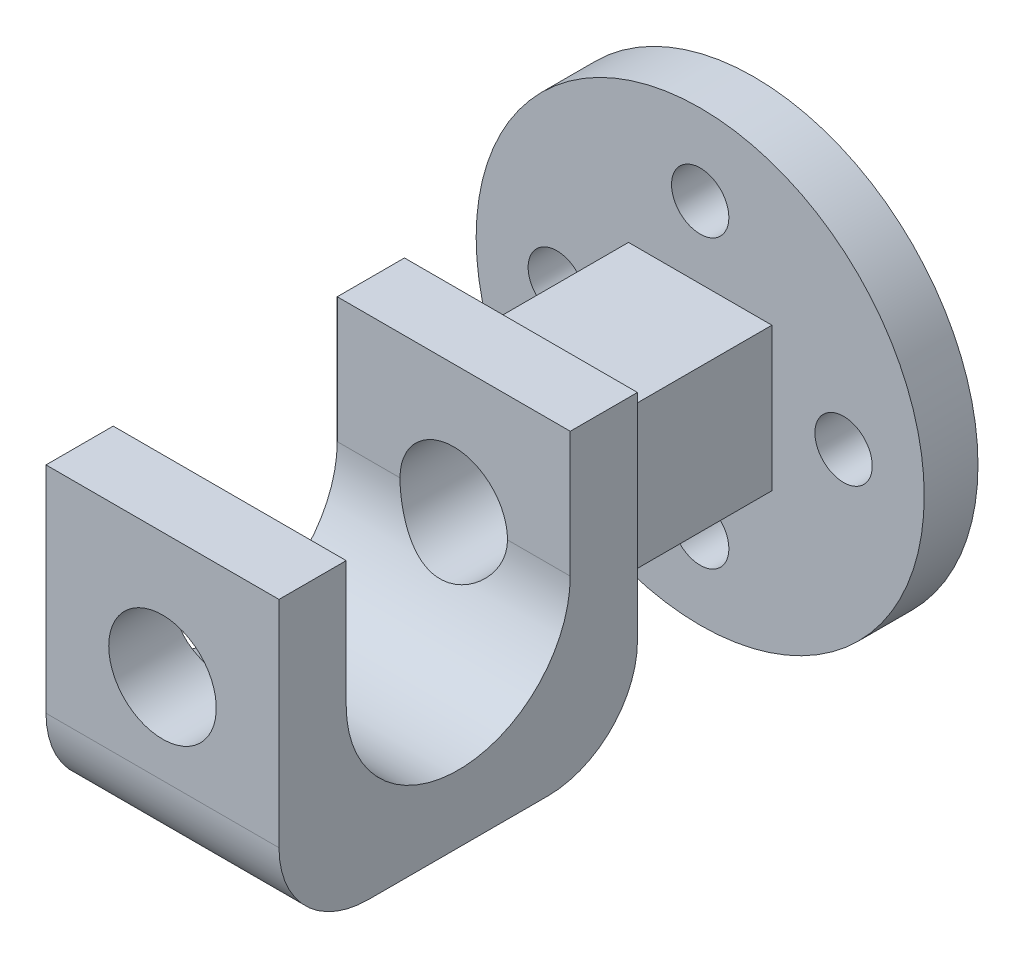
SolidWorks part; units mm, degrees
ref_plane "前视基准面" through (0, 0, 0) normal (0, 0, 1) x (1, 0, 0)
ref_plane "上视基准面" through (0, 0, 0) normal (0, 1, 0) x (1, 0, 0)
ref_plane "右视基准面" through (0, 0, 0) normal (1, 0, 0) x (0, 0, -1)
sketch "草图1" plane through (0, 0, 0) normal (0, 0, 1) x (1, 0, 0)
  circle A0 centre (0, 0) radius 12.5
  circle A1 centre (0, 0) radius 8 construction
  circle A2 centre (0, 8) radius 1.6
  circle A3 centre (8, 0) radius 1.6
  circle A4 centre (0, -8) radius 1.6
  circle A5 centre (-8, 0) radius 1.6
  point P15 (0, 0)
  dimension "D1" = 25
  dimension "D2" = 16
  dimension "D3" = 3.2
  dimension "D4" = 4
extrude "凸台-拉伸1" add sketch "草图1" along normal blind 3
sketch "草图2" plane through (0, 0, 3) normal (0, 0, 1) x (1, 0, 0)
  line L1 (4, -4) -> (-4, -4)
  line L2 (4, -4) -> (4, 4)
  line L3 (4, 4) -> (-4, 4)
  line L4 (-4, -4) -> (-4, 4)
  line L5 (0, 4) -> (0, -4) construction
  line L6 (4, 0) -> (-4, 0) construction
  point P0 (0, 0)
  dimension "D1" = 8
  dimension "D2" = 8
extrude "凸台-拉伸2" add sketch "草图2" along normal blind 10
sketch "草图4" plane through (0, 0, 0) normal (-1, 0, 0) x (0, 0, 1)
  line L0 (0, 0) -> (27.7393, 0) construction
  line L5 (13, 4) -> (13, -4) construction
  line L6 (33, -10) -> (13, -10)
  line L7 (33, -10) -> (33, 10)
  line L8 (33, 10) -> (13, 10)
  line L9 (13, -10) -> (13, 10)
  line L10 (23, 10) -> (23, -10) construction
  line L11 (33, 0) -> (13, 0) construction
  line L12 (16.75, 0) -> (16.75, 10)
  line L17 (23, 10) -> (23, -10) construction
  line L18 (29.25, 0) -> (16.5, 0) construction
  line L19 (29.25, 0) -> (29.25, 10)
  line L21 (13, 10) -> (33, 10)
  line L22 (13, 10) -> (13, 7)
  line L23 (13, 7) -> (33, 7)
  line L24 (33, 10) -> (33, 7)
  circle A0 centre (23, 0) radius 6.25
  point P2 (23, 0)
  point P9 (23, 0)
  dimension "D2" = 12.5
  dimension "D1" = 20
  dimension "D3" = 20
  dimension "D4" = 3
extrude "凸台-拉伸3" add sketch "草图4" against normal mid plane 13 contours L12 A0 L19 L8 L7 L6 L9
sketch "草图5" plane through (0, 0, 0) normal (0, 0, -1) x (-1, 0, 0)
  circle A0 centre (0, 0) radius 3
  dimension "D1" = 6
extrude "切除-拉伸1" cut sketch "草图5" against normal through all
fillet "圆角1" radius 5 2 edges at (0, -10, 13) (0, -10, 33)
